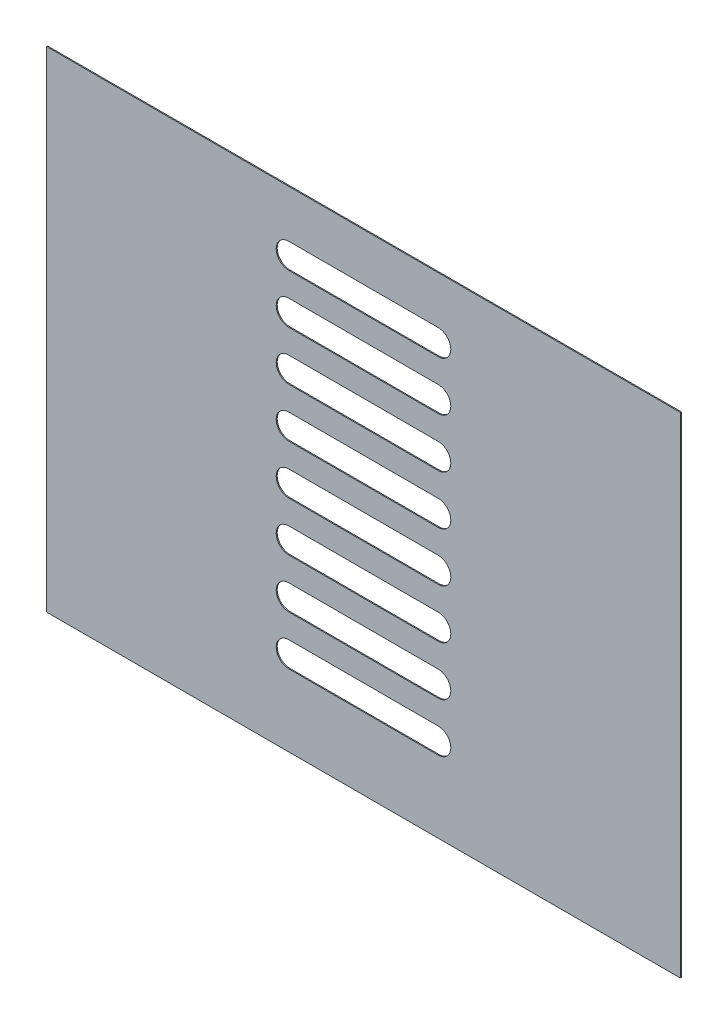
SolidWorks part; units mm, degrees
ref_plane "Front Plane" through (0, 0, 0) normal (0, 0, 1) x (1, 0, 0)
ref_plane "Top Plane" through (0, 0, 0) normal (0, 1, 0) x (1, 0, 0)
ref_plane "Right Plane" through (0, 0, 0) normal (1, 0, 0) x (0, 0, -1)
sketch "Sketch1" plane through (0, 0, 0) normal (0, 0, 1) x (1, 0, 0)
  line L1 (0, 0) -> (509, 0)
  line L2 (0, 0) -> (0, 393.5)
  line L3 (0, 393.5) -> (509, 393.5)
  line L4 (509, 0) -> (509, 393.5)
  line L5 (194.5, 305.5458) -> (314.5, 305.5458) construction
  line L6 (194.5, 295.4254) -> (314.5, 295.4254)
  line L7 (194.5, 345.1443) -> (314.5, 345.1443) construction
  line L8 (194.5, 355.2647) -> (314.5, 355.2647)
  line L9 (194.5, 335.0239) -> (314.5, 335.0239)
  line L10 (194.5, 315.6661) -> (314.5, 315.6661)
  line L14 (194.5, 265.9443) -> (314.5, 265.9443) construction
  line L15 (194.5, 276.0647) -> (314.5, 276.0647)
  line L16 (194.5, 255.8239) -> (314.5, 255.8239)
  line L18 (194.5, 226.3458) -> (314.5, 226.3458) construction
  line L19 (194.5, 216.2254) -> (314.5, 216.2254)
  line L20 (194.5, 236.4661) -> (314.5, 236.4661)
  line L22 (194.5, 147.1458) -> (314.5, 147.1458) construction
  line L23 (194.5, 137.0254) -> (314.5, 137.0254)
  line L24 (194.5, 157.2661) -> (314.5, 157.2661)
  line L25 (194.5, 186.7443) -> (314.5, 186.7443) construction
  line L26 (194.5, 196.8647) -> (314.5, 196.8647)
  line L27 (194.5, 176.6239) -> (314.5, 176.6239)
  line L28 (194.5, 226.3458) -> (314.5, 226.3458) construction
  line L29 (194.5, 216.2254) -> (314.5, 216.2254)
  line L30 (194.5, 236.4661) -> (314.5, 236.4661)
  line L32 (194.5, 67.9458) -> (314.5, 67.9458) construction
  line L33 (194.5, 57.8254) -> (314.5, 57.8254)
  line L34 (194.5, 78.0661) -> (314.5, 78.0661)
  line L35 (194.5, 107.5443) -> (314.5, 107.5443) construction
  line L36 (194.5, 117.6647) -> (314.5, 117.6647)
  line L37 (194.5, 97.4239) -> (314.5, 97.4239)
  line L38 (194.5, 147.1458) -> (314.5, 147.1458) construction
  line L39 (194.5, 137.0254) -> (314.5, 137.0254)
  line L40 (194.5, 157.2661) -> (314.5, 157.2661)
  line L41 (194.5, 186.7443) -> (314.5, 186.7443) construction
  line L42 (194.5, 196.8647) -> (314.5, 196.8647)
  line L43 (194.5, 176.6239) -> (314.5, 176.6239)
  arc A0 (194.5, 355.2647) -> (194.5, 335.0239) centre (194.5, 345.1443) ccw
  arc A1 (314.5, 335.0239) -> (314.5, 355.2647) centre (314.5, 345.1443) ccw
  arc A2 (194.5, 295.4254) -> (194.5, 315.6661) centre (194.5, 305.5458) cw
  arc A3 (314.5, 315.6661) -> (314.5, 295.4254) centre (314.5, 305.5458) cw
  arc A4 (194.5, 276.0647) -> (194.5, 255.8239) centre (194.5, 265.9443) ccw
  arc A5 (314.5, 255.8239) -> (314.5, 276.0647) centre (314.5, 265.9443) ccw
  arc A6 (194.5, 216.2254) -> (194.5, 236.4661) centre (194.5, 226.3458) cw
  arc A7 (314.5, 236.4661) -> (314.5, 216.2254) centre (314.5, 226.3458) cw
  arc A8 (194.5, 137.0254) -> (194.5, 157.2661) centre (194.5, 147.1458) cw
  arc A9 (314.5, 157.2661) -> (314.5, 137.0254) centre (314.5, 147.1458) cw
  arc A10 (194.5, 196.8647) -> (194.5, 176.6239) centre (194.5, 186.7443) ccw
  arc A11 (314.5, 176.6239) -> (314.5, 196.8647) centre (314.5, 186.7443) ccw
  arc A12 (194.5, 216.2254) -> (194.5, 236.4661) centre (194.5, 226.3458) cw
  arc A13 (314.5, 236.4661) -> (314.5, 216.2254) centre (314.5, 226.3458) cw
  arc A14 (194.5, 57.8254) -> (194.5, 78.0661) centre (194.5, 67.9458) cw
  arc A15 (314.5, 78.0661) -> (314.5, 57.8254) centre (314.5, 67.9458) cw
  arc A16 (194.5, 117.6647) -> (194.5, 97.4239) centre (194.5, 107.5443) ccw
  arc A17 (314.5, 97.4239) -> (314.5, 117.6647) centre (314.5, 107.5443) ccw
  arc A18 (194.5, 137.0254) -> (194.5, 157.2661) centre (194.5, 147.1458) cw
  arc A19 (314.5, 157.2661) -> (314.5, 137.0254) centre (314.5, 147.1458) cw
  arc A20 (194.5, 196.8647) -> (194.5, 176.6239) centre (194.5, 186.7443) ccw
  arc A21 (314.5, 176.6239) -> (314.5, 196.8647) centre (314.5, 186.7443) ccw
  point P8 (254.5, 393.5)
  point P10 (254.5, 345.1443)
  point P17 (254.5, 305.5458)
  point P27 (254.5, 265.9443)
  point P36 (254.5, 226.3458)
  point P45 (254.5, 147.1458)
  point P52 (254.5, 186.7443)
  point P67 (254.5, 67.9458)
  point P74 (254.5, 107.5443)
extrude "Boss-Extrude1" add sketch "Sketch1" along normal blind 0.8 contours L1 L4 L3 L2 A17 L37 A16 L36 A11 L27 A10 L26 A5 L16 A4 L15 A1 L9 A0 L8 L10 A3 L6 A2 L20 A7 L19 A6 L24 A9 L23 A8 L34 A15 L33 A14
